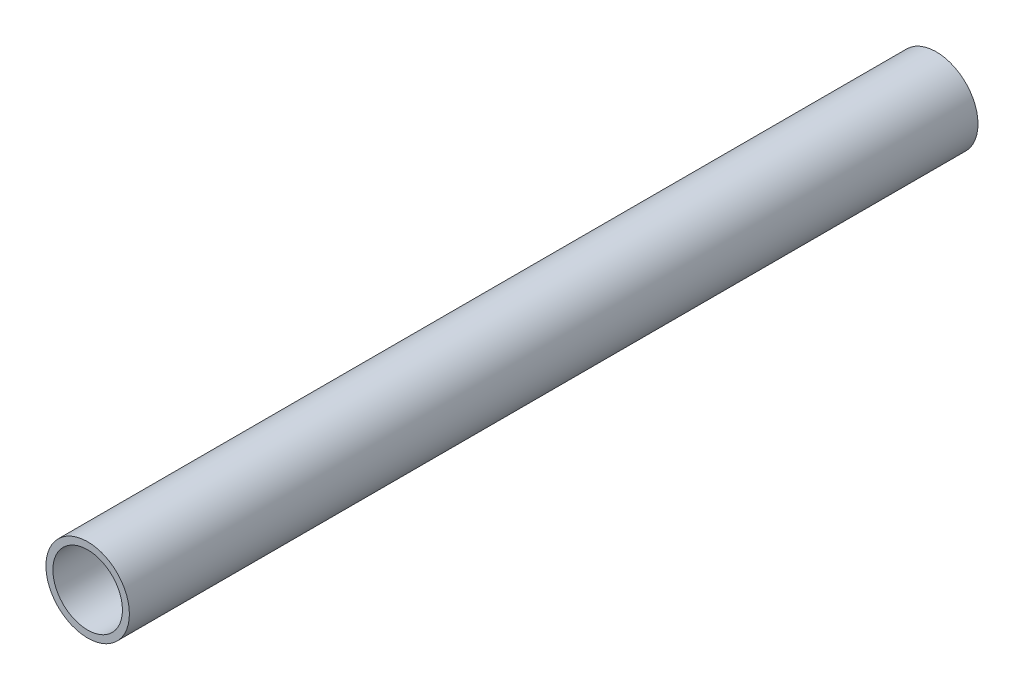
SolidWorks part; units mm, degrees
material "Teak"
ref_plane "Front Plane" through (0, 0, 0) normal (0, 0, 1) x (1, 0, 0)
ref_plane "Top Plane" through (0, 0, 0) normal (0, 1, 0) x (1, 0, 0)
ref_plane "Right Plane" through (0, 0, 0) normal (1, 0, 0) x (0, 0, -1)
sketch "Sketch2" plane through (0, 0, 0) normal (0, 0, 1) x (1, 0, 0)
  circle A0 centre (0, 0) radius 25
  circle A1 centre (0, 0) radius 30
  point P4 (0, 0)
  dimension "D1" = 50
  dimension "D2" = 60
extrude "Boss-Extrude1" add sketch "Sketch2" against normal blind 610
